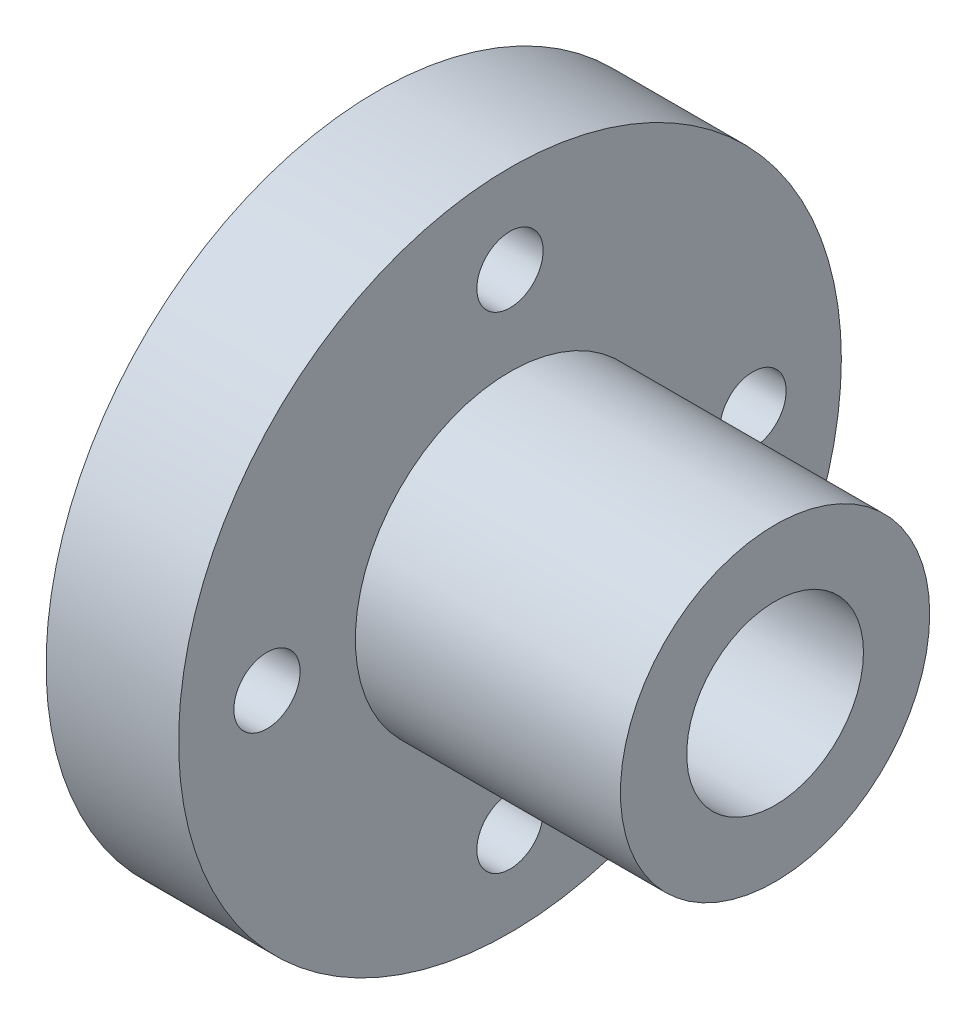
SolidWorks part; units mm, degrees
material "Простая углеродистая сталь"
ref_plane "Спереди" through (0, 0, 0) normal (0, 0, 1) x (1, 0, 0)
ref_plane "Сверху" through (0, 0, 0) normal (0, 1, 0) x (1, 0, 0)
ref_plane "Справа" through (0, 0, 0) normal (1, 0, 0) x (0, 0, -1)
sketch "Эскиз1" plane through (0, 0, 0) normal (0, 0, 1) x (1, 0, 0)
  line L0 (0, 4) -> (0, 7)
  line L1 (0, 7) -> (2, 7)
  line L2 (2, 7) -> (2, 15)
  line L3 (2, 15) -> (8, 15)
  line L4 (8, 15) -> (8, 7)
  line L5 (8, 0) -> (0, 0) construction
  line L6 (0, 4) -> (20, 4)
  line L7 (8, 7) -> (20, 7)
  line L8 (20, 7) -> (20, 4)
  dimension "D1" = 8
  dimension "D2" = 14
  dimension "D3" = 20
  dimension "D4" = 30
  dimension "D5" = 2
  dimension "D6" = 6
revolve "Повернуть1" add sketch "Эскиз1" angle 360 about L5
sketch "Эскиз2" plane through (2, 0, 0) normal (-1, 0, 0) x (0, 0, 1)
  circle A0 centre (0, 0) radius 11 construction
  circle A1 centre (0, 11) radius 1.5
  circle A2 centre (-11, 0) radius 1.5
  circle A3 centre (0, -11) radius 1.5
  circle A4 centre (11, 0) radius 1.5
  dimension "D1" = 3
  dimension "D2" = 22
extrude "Вырез-Вытянуть1" cut sketch "Эскиз2" against normal through all
